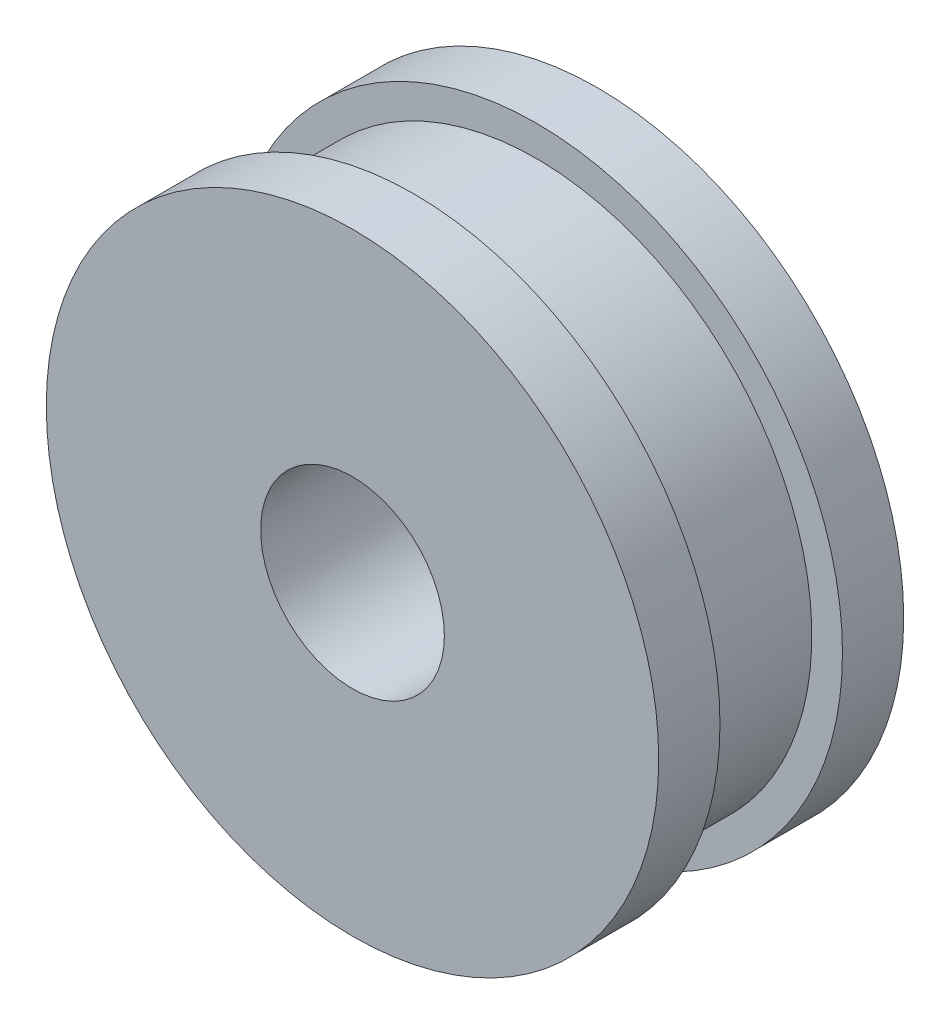
SolidWorks part; units mm, degrees
ref_plane "Front Plane" through (0, 0, 0) normal (0, 0, 1) x (1, 0, 0)
ref_plane "Top Plane" through (0, 0, 0) normal (0, 1, 0) x (1, 0, 0)
ref_plane "Right Plane" through (0, 0, 0) normal (1, 0, 0) x (0, 0, -1)
sketch "Sketch1" plane through (0, 0, 0) normal (0, 0, 1) x (1, 0, 0)
  circle A0 centre (0, 0) radius 50
  circle A1 centre (0, 0) radius 15
  dimension "D1" = 100
  dimension "D2" = 30
extrude "Boss-Extrude1" add sketch "Sketch1" along normal blind 40
sketch "Sketch2" plane through (0, 0, 0) normal (1, 0, 0) x (0, 0, -1)
  line L0 (0, 50) -> (-40, 50) construction
  line L1 (-30, 50) -> (-10, 50)
  line L2 (-30, 50) -> (-30, 45)
  line L3 (-30, 45) -> (-10, 45)
  line L4 (-10, 50) -> (-10, 45)
  line L5 (-40, -50) -> (0, -50) construction
  line L6 (-10, -50) -> (-30, -50)
  line L7 (-10, -50) -> (-10, -45)
  line L8 (-10, -45) -> (-30, -45)
  line L9 (-30, -50) -> (-30, -45)
  line L10 (0, -50) -> (0, 50) construction
  line L11 (-40, 50) -> (-40, -50) construction
  line L12 (46.8793, 0) -> (-110.3098, 0) construction
  dimension "D1" = 5
  dimension "D2" = 20
  dimension "D3" = 10
  dimension "D4" = 10
revolve "Cut-Revolve1" cut sketch "Sketch2" angle 360 about L12
